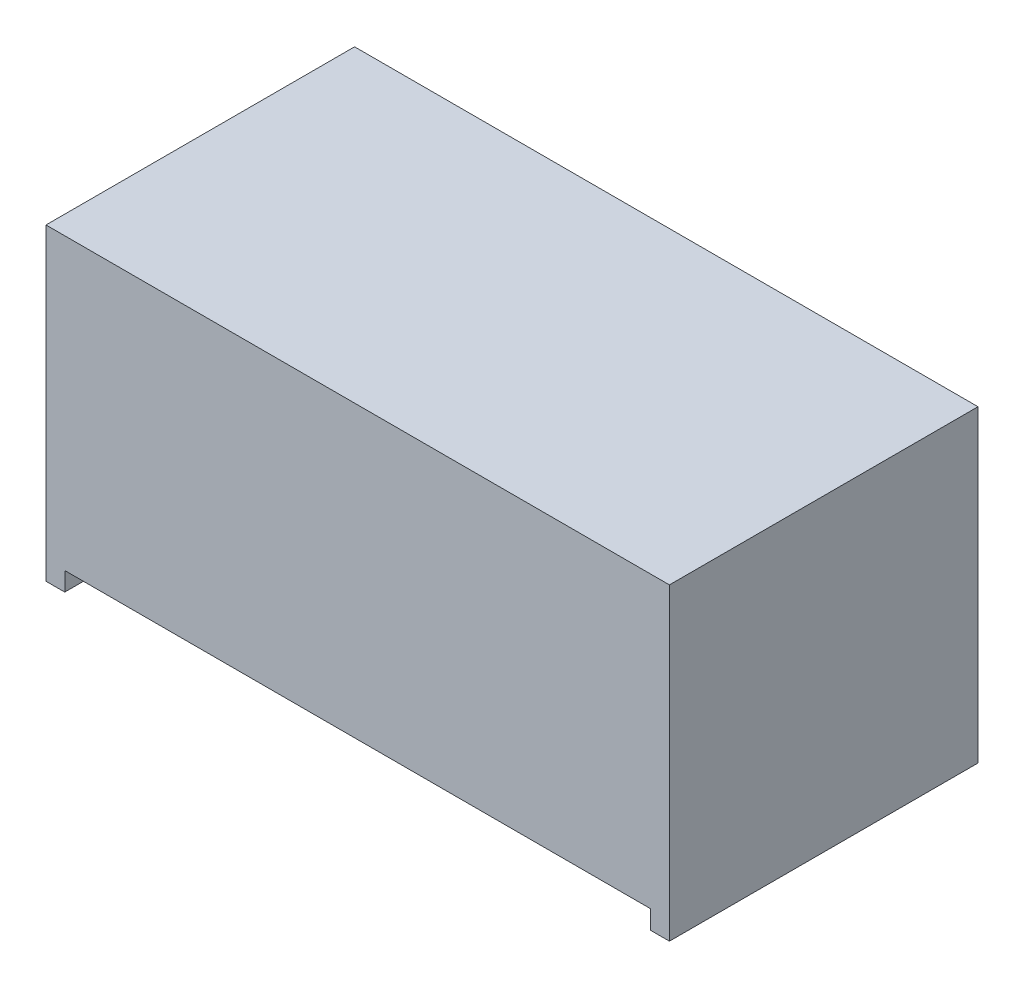
SolidWorks part; units mm, degrees
ref_plane "Front Plane" through (0, 0, 0) normal (0, 0, 1) x (1, 0, 0)
ref_plane "Top Plane" through (0, 0, 0) normal (0, 1, 0) x (1, 0, 0)
ref_plane "Right Plane" through (0, 0, 0) normal (1, 0, 0) x (0, 0, -1)
sketch "Sketch1" plane through (0, 0, 0) normal (0, 1, 0) x (1, 0, 0)
  line L1 (-10, 4.95) -> (10, 4.95)
  line L2 (-10, 4.95) -> (-10, -4.95)
  line L3 (-10, -4.95) -> (10, -4.95)
  line L4 (10, 4.95) -> (10, -4.95)
  line L5 (-10, 4.95) -> (10, -4.95) construction
  line L6 (-10, -4.95) -> (10, 4.95) construction
  point P0 (0, 0)
  dimension "D1" = 20
  dimension "D2" = 9.9
extrude "Boss-Extrude1" add sketch "Sketch1" along normal blind 9.3
sketch "Sketch2" plane through (0, 0, 0) normal (0, -1, 0) x (1, 0, 0)
  line L0 (10, -4.95) -> (-10, -4.95) construction
  line L1 (-10, 4.95) -> (-9.3983, 4.95)
  line L2 (-10, 4.95) -> (-10, -4.95)
  line L3 (-10, -4.95) -> (-9.3983, -4.95)
  line L4 (-9.3983, 4.95) -> (-9.3983, -4.95)
  line L6 (10, 4.95) -> (9.3983, 4.95)
  line L7 (10, 4.95) -> (10, -4.95)
  line L8 (10, -4.95) -> (9.3983, -4.95)
  line L9 (9.3983, 4.95) -> (9.3983, -4.95)
extrude "Boss-Extrude2" add sketch "Sketch2" along normal blind 0.6
